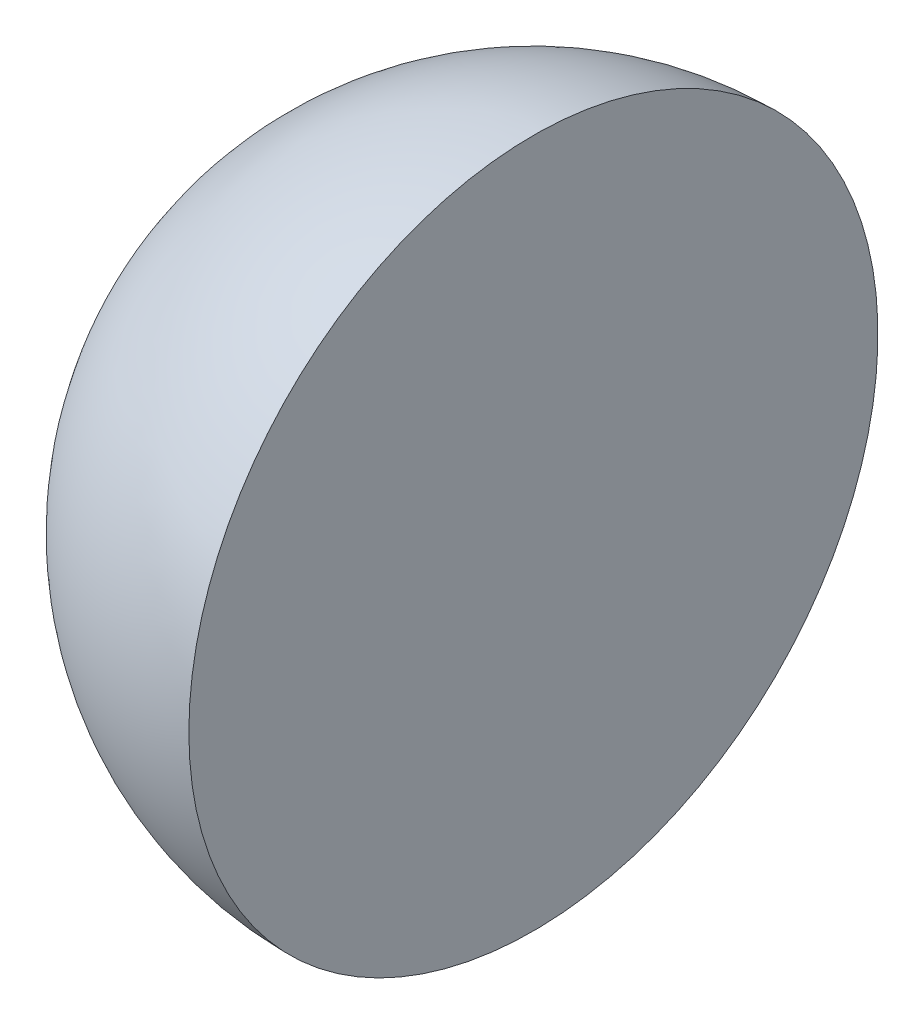
SolidWorks part; units mm, degrees
material "Pine"
ref_plane "Front Plane" through (0, 0, 0) normal (0, 0, 1) x (1, 0, 0)
ref_plane "Top Plane" through (0, 0, 0) normal (0, 1, 0) x (1, 0, 0)
ref_plane "Right Plane" through (0, 0, 0) normal (1, 0, 0) x (0, 0, -1)
sketch "Sketch2" plane through (0, 0, 0) normal (1, 0, 0) x (0, 0, -1)
  line L0 (-25.4, 0) -> (25.4, 0)
  arc A0 (25.4, 0) -> (-25.4, 0) centre (0, 0) cw
  point P4 (-25.4, -7.3987)
  point P5 (0, 0)
  dimension "D1" = 50.8
revolve "Revolve1" add sketch "Sketch2" angle 180 about L0
